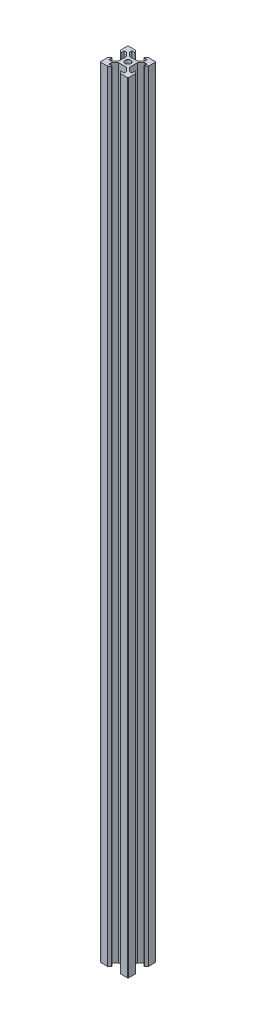
SolidWorks part; units mm, degrees
ref_plane "Front Plane" through (0, 0, 0) normal (0, 0, 1) x (1, 0, 0)
ref_plane "Top Plane" through (0, 0, 0) normal (0, 1, 0) x (1, 0, 0)
ref_plane "Right Plane" through (0, 0, 0) normal (1, 0, 0) x (0, 0, -1)
sketch "Sketch1" plane through (0, 0, 0) normal (1, 0, 0) x (0, 0, -1)
  line L0 (0, 0) -> (0, 558.8)
  dimension "D1" = 558.8
other "Vslot2020 2020(5)"
ref_plane "Plane5" through (0, 0, 0) normal (0, 1, 0) x (0, 0, 1)
sketch "Sketch2" plane through (0, 0, 0) normal (0, 1, 0) x (0, 0, 1)
  line L58 (13.9, 7.1491) -> (13.9, 12.8445)
  line L59 (13.9, 12.8445) -> (16.5585, 15.4922)
  line L60 (16.5585, 15.4922) -> (16.5507, 15.5)
  line L61 (16.5507, 15.5) -> (18.2, 15.5)
  line L62 (18.2, 15.5) -> (18.2, 13.12)
  line L63 (18.2, 13.12) -> (18.5344, 13.12)
  line L64 (18.5344, 13.12) -> (20, 14.58)
  line L65 (20, 14.58) -> (20, 19.5)
  line L66 (19.5, 20) -> (14.575, 20)
  line L67 (14.575, 20) -> (13.12, 18.545)
  line L68 (13.12, 18.545) -> (13.12, 18.2)
  line L69 (13.12, 18.2) -> (15.5, 18.2)
  line L70 (15.5, 18.2) -> (15.5, 16.555)
  line L71 (15.5, 16.555) -> (12.8341, 13.9)
  line L72 (12.8341, 13.9) -> (7.155, 13.9)
  line L73 (7.155, 13.9) -> (4.5, 16.555)
  line L74 (4.5, 16.555) -> (4.5, 18.2)
  line L75 (4.5, 18.2) -> (6.875, 18.2)
  line L76 (6.875, 18.2) -> (6.875, 18.545)
  line L77 (6.875, 18.545) -> (5.42, 20)
  line L78 (5.42, 20) -> (0.5, 20)
  line L79 (0, 19.5) -> (0, 14.58)
  line L80 (0, 14.58) -> (1.46, 13.12)
  line L81 (1.46, 13.12) -> (1.8, 13.12)
  line L82 (1.8, 13.12) -> (1.8, 15.5)
  line L83 (1.8, 15.5) -> (3.445, 15.5)
  line L84 (3.445, 15.5) -> (3.4393, 15.4943)
  line L85 (3.4393, 15.4943) -> (6.0943, 12.8393)
  line L86 (6.0943, 12.8393) -> (6.1, 12.845)
  line L87 (6.1, 12.845) -> (6.1, 7.1491)
  line L88 (6.1, 7.1491) -> (3.4393, 4.5)
  line L89 (3.4393, 4.5) -> (1.8, 4.5)
  line L90 (1.8, 4.5) -> (1.8, 6.88)
  line L91 (1.8, 6.88) -> (1.46, 6.88)
  line L92 (1.46, 6.88) -> (0, 5.42)
  line L93 (0, 5.42) -> (0, 0.5)
  line L94 (0.5, 0) -> (5.42, 0)
  line L95 (5.42, 0) -> (6.875, 1.455)
  line L96 (6.875, 1.455) -> (6.875, 1.8)
  line L97 (6.875, 1.8) -> (4.5, 1.8)
  line L98 (4.5, 1.8) -> (4.5, 3.4393)
  line L99 (4.5, 3.4393) -> (7.1583, 6.0861)
  line L100 (7.1583, 6.0861) -> (7.1445, 6.1)
  line L101 (7.1445, 6.1) -> (12.8546, 6.1)
  line L102 (12.8546, 6.1) -> (12.8412, 6.0865)
  line L103 (12.8412, 6.0865) -> (15.4997, 3.4375)
  line L104 (15.4997, 3.4375) -> (15.5, 3.4377)
  line L105 (15.5, 3.4377) -> (15.5, 1.8)
  line L106 (15.5, 1.8) -> (13.12, 1.8)
  line L107 (13.12, 1.8) -> (13.12, 1.455)
  line L108 (13.12, 1.455) -> (14.575, 0)
  line L109 (14.575, 0) -> (19.5, 0)
  line L110 (20, 0.5) -> (20, 5.42)
  line L111 (20, 5.42) -> (18.6069, 6.88)
  line L112 (18.6069, 6.88) -> (18.2, 6.88)
  line L113 (18.2, 6.88) -> (18.2, 4.5)
  line L114 (18.2, 4.5) -> (16.5585, 4.5)
  line L115 (16.5585, 4.5) -> (13.9, 7.1491)
  line L116 (13.9, 7.1491) -> (13.9, 12.8445)
  line L117 (13.9, 12.8445) -> (16.5585, 15.4922)
  line L118 (16.5585, 15.4922) -> (16.5507, 15.5)
  line L119 (16.5507, 15.5) -> (18.2, 15.5)
  line L120 (18.2, 15.5) -> (18.2, 13.12)
  line L121 (18.2, 13.12) -> (18.5344, 13.12)
  line L122 (18.5344, 13.12) -> (20, 14.58)
  line L123 (20, 14.58) -> (20, 19.5)
  line L124 (19.5, 20) -> (14.575, 20)
  line L125 (14.575, 20) -> (13.12, 18.545)
  line L126 (13.12, 18.545) -> (13.12, 18.2)
  line L127 (13.12, 18.2) -> (15.5, 18.2)
  line L128 (15.5, 18.2) -> (15.5, 16.555)
  line L129 (15.5, 16.555) -> (12.8341, 13.9)
  line L130 (12.8341, 13.9) -> (7.155, 13.9)
  line L131 (7.155, 13.9) -> (4.5, 16.555)
  line L132 (4.5, 16.555) -> (4.5, 18.2)
  line L133 (4.5, 18.2) -> (6.875, 18.2)
  line L134 (6.875, 18.2) -> (6.875, 18.545)
  line L135 (6.875, 18.545) -> (5.42, 20)
  line L136 (5.42, 20) -> (0.5, 20)
  line L137 (0, 19.5) -> (0, 14.58)
  line L138 (0, 14.58) -> (1.46, 13.12)
  line L139 (1.46, 13.12) -> (1.8, 13.12)
  line L140 (1.8, 13.12) -> (1.8, 15.5)
  line L141 (1.8, 15.5) -> (3.445, 15.5)
  line L142 (3.445, 15.5) -> (3.4393, 15.4943)
  line L143 (3.4393, 15.4943) -> (6.0943, 12.8393)
  line L144 (6.0943, 12.8393) -> (6.1, 12.845)
  line L145 (6.1, 12.845) -> (6.1, 7.1491)
  line L146 (6.1, 7.1491) -> (3.4393, 4.5)
  line L147 (3.4393, 4.5) -> (1.8, 4.5)
  line L148 (1.8, 4.5) -> (1.8, 6.88)
  line L149 (1.8, 6.88) -> (1.46, 6.88)
  line L150 (1.46, 6.88) -> (0, 5.42)
  line L151 (0, 5.42) -> (0, 0.5)
  line L152 (0.5, 0) -> (5.42, 0)
  line L153 (5.42, 0) -> (6.875, 1.455)
  line L154 (6.875, 1.455) -> (6.875, 1.8)
  line L155 (6.875, 1.8) -> (4.5, 1.8)
  line L156 (4.5, 1.8) -> (4.5, 3.4393)
  line L157 (4.5, 3.4393) -> (7.1583, 6.0861)
  line L158 (7.1583, 6.0861) -> (7.1445, 6.1)
  line L159 (7.1445, 6.1) -> (12.8546, 6.1)
  line L160 (12.8546, 6.1) -> (12.8412, 6.0865)
  line L161 (12.8412, 6.0865) -> (15.4997, 3.4375)
  line L162 (15.4997, 3.4375) -> (15.5, 3.4377)
  line L163 (15.5, 3.4377) -> (15.5, 1.8)
  line L164 (15.5, 1.8) -> (13.12, 1.8)
  line L165 (13.12, 1.8) -> (13.12, 1.455)
  line L166 (13.12, 1.455) -> (14.575, 0)
  line L167 (14.575, 0) -> (19.5, 0)
  line L168 (20, 0.5) -> (20, 5.42)
  line L169 (20, 5.42) -> (18.6069, 6.88)
  line L170 (18.6069, 6.88) -> (18.2, 6.88)
  line L171 (18.2, 6.88) -> (18.2, 4.5)
  line L172 (18.2, 4.5) -> (16.5585, 4.5)
  line L173 (16.5585, 4.5) -> (13.9, 7.1491)
  circle A0 centre (10, 10) radius 2.0746 construction
  circle A1 centre (10, 10) radius 2.0746
  arc A4 (20, 19.5) -> (19.5, 20) centre (19.5, 19.5) ccw
  arc A5 (0.5, 20) -> (0, 19.5) centre (0.5, 19.5) ccw
  arc A6 (0, 0.5) -> (0.5, 0) centre (0.5, 0.5) ccw
  arc A7 (19.5, 0) -> (20, 0.5) centre (19.5, 0.5) ccw
  arc A8 (20, 19.5) -> (19.5, 20) centre (19.5, 19.5) ccw
  arc A9 (0.5, 20) -> (0, 19.5) centre (0.5, 19.5) ccw
  arc A10 (0, 0.5) -> (0.5, 0) centre (0.5, 0.5) ccw
  arc A11 (19.5, 0) -> (20, 0.5) centre (19.5, 0.5) ccw
  point P16 (0, 0)
  dimension "D1" = 0
ref_plane "Plane6" through (0, 0, 9.9946) normal (0, 0, 1) x (1, 0, 0)
ref_plane "Plane7" through (9.997, 0, 0) normal (1, 0, 0) x (0, 0, -1)
